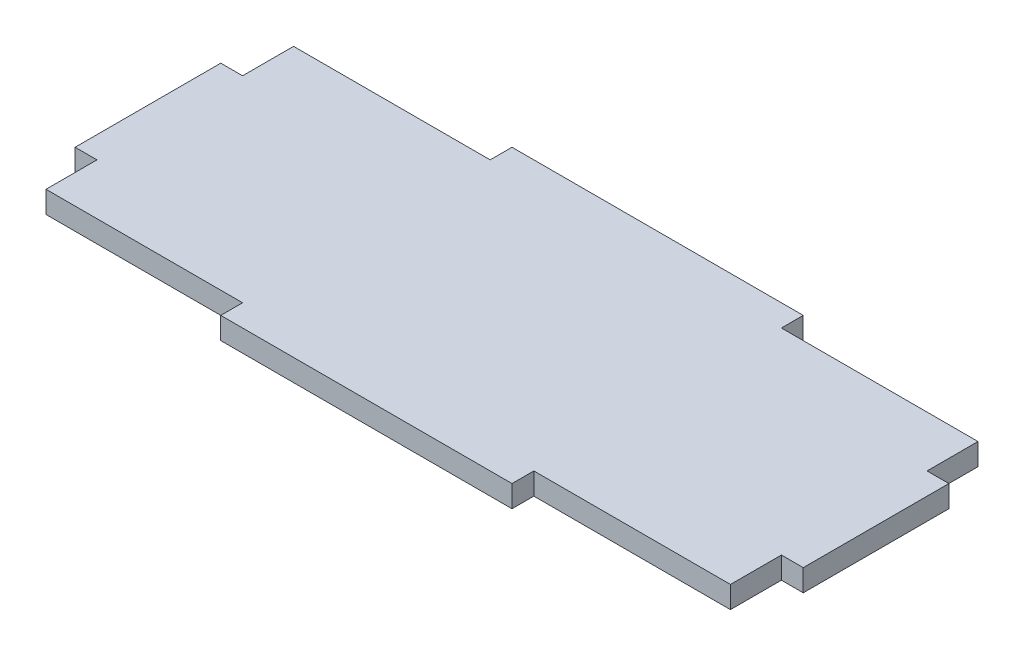
SolidWorks part; units mm, degrees
ref_plane "Plan de face" through (0, 0, 0) normal (0, 0, 1) x (1, 0, 0)
ref_plane "Plan de dessus" through (0, 0, 0) normal (0, 1, 0) x (1, 0, 0)
ref_plane "Plan de droite" through (0, 0, 0) normal (1, 0, 0) x (0, 0, -1)
sketch "Esquisse1" plane through (0, 0, 0) normal (0, 1, 0) x (1, 0, 0)
  line L0 (-12.6545, 12.4681) -> (27.3455, 12.4681)
  line L1 (-12.6545, -27.5319) -> (27.3455, -27.5319)
  line L2 (-42.6545, 2.4681) -> (-42.6545, -17.5319)
  line L4 (57.3455, 2.4681) -> (57.3455, -17.5319)
  line L7 (-42.6545, 2.4681) -> (-39.6545, 2.4681)
  line L8 (-39.6545, 9.4681) -> (-39.6545, 2.4681)
  line L11 (-42.6545, -17.5319) -> (-39.6545, -17.5319)
  line L12 (-39.6545, -24.5319) -> (-39.6545, -17.5319)
  line L14 (54.3455, 9.4681) -> (54.3455, 2.4681)
  line L15 (54.3455, 2.4681) -> (57.3455, 2.4681)
  line L17 (57.3455, -17.5319) -> (54.3455, -17.5319)
  line L20 (54.3455, -17.5319) -> (54.3455, -24.5319)
  line L23 (-39.6545, 9.4681) -> (-12.6545, 9.4681)
  line L24 (-12.6545, 12.4681) -> (-12.6545, 9.4681)
  line L27 (54.3455, 9.4681) -> (27.3455, 9.4681)
  line L28 (27.3455, 12.4681) -> (27.3455, 9.4681)
  line L31 (-39.6545, -24.5319) -> (-12.6545, -24.5319)
  line L32 (-12.6545, -27.5319) -> (-12.6545, -24.5319)
  line L33 (54.3455, -24.5319) -> (27.3455, -24.5319)
  line L36 (27.3455, -24.5319) -> (27.3455, -27.5319)
  dimension "D1" = 40
  dimension "D2" = 100
  dimension "D3" = 3
  dimension "D4" = 27
  dimension "D5" = 7
  dimension "D6" = 7
extrude "Boss.-Extru.1" add sketch "Esquisse1" along normal blind 3
